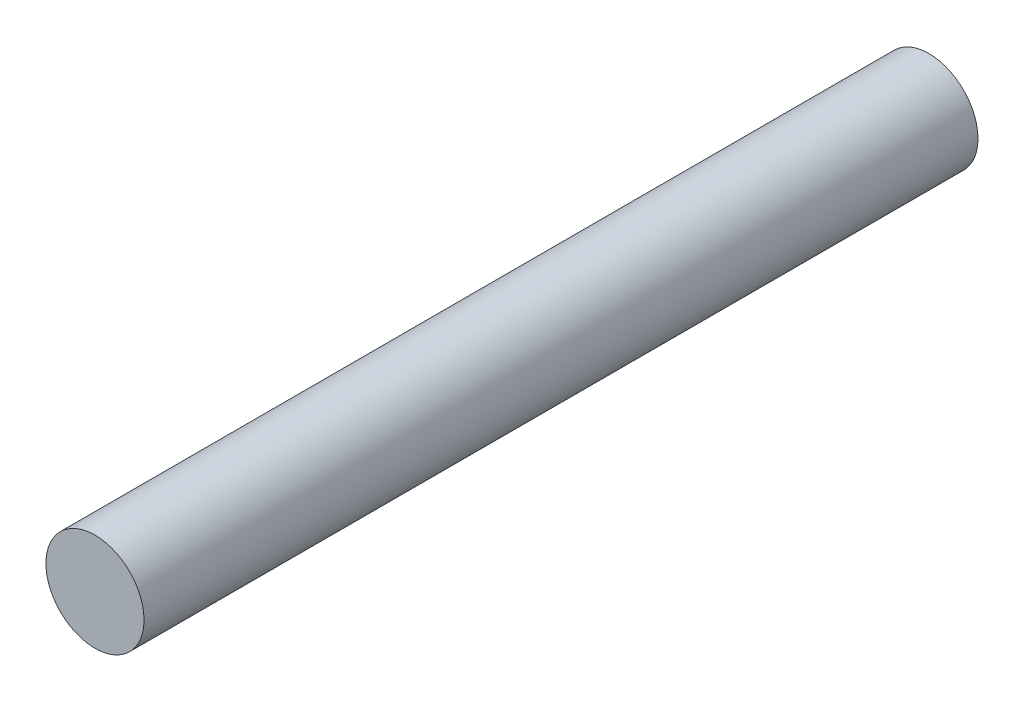
SolidWorks part; units mm, degrees
ref_plane "前视基准面" through (0, 0, 0) normal (0, 0, 1) x (1, 0, 0)
ref_plane "上视基准面" through (0, 0, 0) normal (0, 1, 0) x (1, 0, 0)
ref_plane "右视基准面" through (0, 0, 0) normal (1, 0, 0) x (0, 0, -1)
sketch "草图1" plane through (0, 0, 0) normal (0, 0, 1) x (1, 0, 0)
  circle A0 centre (0, 0) radius 4
extrude "凸台-拉伸1" add sketch "草图1" along normal blind 68
